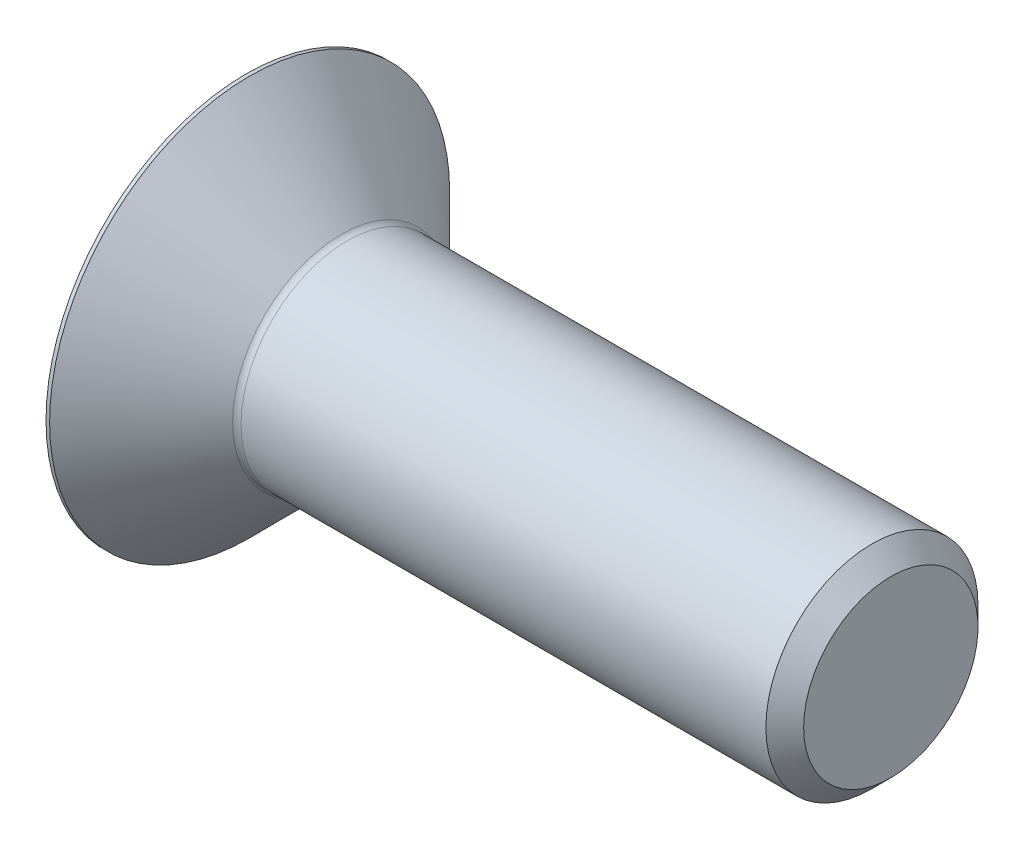
SolidWorks part; units mm, degrees
ref_plane "Plane1" through (0, 0, 0) normal (0, 0, 1) x (1, 0, 0)
ref_plane "Plane2" through (0, 0, 0) normal (0, 1, 0) x (1, 0, 0)
ref_plane "Plane3" through (0, 0, 0) normal (1, 0, 0) x (0, 0, -1)
sketch "BodySke" plane through (0, 0, 0) normal (0, 0, 1) x (1, 0, 0)
  line L0 (0, 0) -> (0, 4.715)
  line L1 (0.885, 4.715) -> (3.1, 2.5)
  line L2 (0, 4.715) -> (0.885, 4.715)
  line L3 (3.1, 2.5) -> (15.555, 2.5)
  line L4 (16, 2.055) -> (16, 0)
  line L5 (16, 0) -> (0, 0)
  line L6 (0, 0) -> (127, 0) construction
  line L7 (0.885, -4.715) -> (3.1, -2.5) construction
  line L8 (16, 2.055) -> (15.555, 2.5)
  line L9 (0, -4.715) -> (0.885, -4.715) construction
  line L10 (16, -2.055) -> (15.555, -2.5) construction
  line L11 (3.9, 8.85) -> (3.9, -13.375) construction
  line L12 (0, 19.05) -> (0, -3.175) construction
  dimension "D1" = 0.885
  dimension "Diameter" = 5
  dimension "Head_ht" = 3.1
  dimension "Length" = 16
  dimension "Body_ch_ang" = 45
  dimension "Head_dia" = 9.43
  dimension "Minor_dia" = 4.11
  dimension "Head_ang" = 90
  dimension "Advance" = 0.8
  dimension "Thread_nom" = 16
revolve "BaseBody" add sketch "BodySke"
cosmetic thread "ThreadCosmetic" [suppressed]
fillet "Fillet1" radius 0.2 1 edges at (3.1, 0, 2.5)
sketch "Sketch2" plane through (0, 0, 0) normal (0, 0, 1) x (1, 0, 0)
  line L0 (0, 1.5) -> (1.9, 1.5)
  line L1 (1.9, 1.5) -> (2.766, 0)
  line L2 (0, 0) -> (127, 0) construction
  line L3 (2.766, 0) -> (0, 0)
  line L4 (0, 0) -> (0, 1.5)
  line L5 (0, -1.5) -> (1.9, -1.5) construction
  line L6 (0, 0) -> (47.625, 0) construction
  line L8 (0, 4.715) -> (0, -4.715) construction
  dimension "D2" = 60
  dimension "PreBroach_depth" = 1.9
  dimension "PreBroach_dia" = 3
revolve "PreBroach" cut sketch "Sketch2" angle 360 about L6
sketch "Sketch3" plane through (0, 0, 0) normal (-1, 0, 0) x (0, 0, 1)
  line L0 (-1.5, -0.866) -> (-1.5, 0.866)
  line L1 (-1.5, 0.866) -> (0, 1.7321)
  line L2 (0, 1.7321) -> (1.5, 0.866)
  line L3 (1.5, 0.866) -> (1.5, -0.866)
  line L4 (1.5, -0.866) -> (0, -1.7321)
  line L5 (0, -1.7321) -> (-1.5, -0.866)
  dimension "D1" = 1.5
  dimension "D2" = 1.5
  dimension "D3" = 3
  dimension "Hex_size" = 3
extrude "Hex" cut sketch "Sketch3" against normal blind 1.9
sketch "ThdSchSke" plane through (0, 0, 0) normal (0, 0, 1) x (1, 0, 0)
  line L0 (5.5, -2.055) -> (5.1884, -2.5)
  line L1 (5.5, -2.055) -> (5.8116, -2.5)
  line L2 (5.8116, -2.5) -> (5.8116, -3.125)
  line L3 (-3.175, 0) -> (5.1513, 0) construction
  line L4 (0, 4.715) -> (0, -4.715) construction
  line L5 (5.8116, -3.125) -> (5.1884, -3.125)
  line L6 (5.1884, -3.125) -> (5.1884, -2.5)
  dimension "Thread_minor" = 4.11
  dimension "Diameter" = 5
  dimension "Start" = 5.5
  dimension "SideAngle" = 55
  dimension "VeeAngle" = 70
  dimension "Overcut" = 6.25
revolve "ThreadSchematic" [suppressed] cut sketch "ThdSchSke" angle 360 about L3
pattern_linear "ThdSchPat" [suppressed]
sketch "Esquisse1" plane through (0, 0, 0) normal (-1, 0, 0) x (0, 0, 1)
  circle A0 centre (0, 0) radius 4.715
extrude "Extrusion1" cut sketch "Esquisse1" against normal blind 0.8
equation "\"Thread_minor@ThreadCosmetic\"  =  \"Minor_dia@BodySke\""
equation "\"D1@Sketch3\" = \"Hex_size@Sketch3\" / 2"
equation "\"D2@Sketch3\" = \"D1@Sketch3\""
equation "\"D3@Sketch3\" = \"Hex_size@Sketch3\""
equation "\"Thread_length@ThreadCosmetic\" = ((sgn( (\"Length@BodySke\" - \"Advance@BodySke\" * 3.0 - \"Head_ht@BodySke\" ) - \"Thread_nom@BodySke\" )-1)*( (\"Length@BodySke\" - \"Advance@BodySke\" * 3.0 - \"Head_ht@BodySke\" ) - \"Thread_nom@BodySke\" ))/-2+ \"Thread_nom@BodySke\""
equation "\"Thread_minor@ThdSchSke\" = \"Minor_dia@BodySke\""
equation "\"Diameter@ThdSchSke\" = \"Diameter@BodySke\""
equation "\"Overcut@ThdSchSke\" = \"Diameter@BodySke\" * 1.25"
equation "\"Start@ThdSchSke\" = 0.000001 + \"Length@BodySke\" - \"Thread_length@ThreadCosmetic\"  '---Countersunk---"
equation "\"Num_threads@ThdSchPat\" = int( \"Thread_length@ThreadCosmetic\" / \"Advance@BodySke\" + 0.999 )  + 1"
equation "\"Advance@ThdSchPat\" = \"Thread_length@ThreadCosmetic\" /  (\"Num_threads@ThdSchPat\" - 1) 'relax it"
equation "\"Num_threads@ThdSchPat\" = \"Num_threads@ThdSchPat\" - sgn( \"Num_threads@ThdSchPat\" - 1) '---chamfered tips only---"
